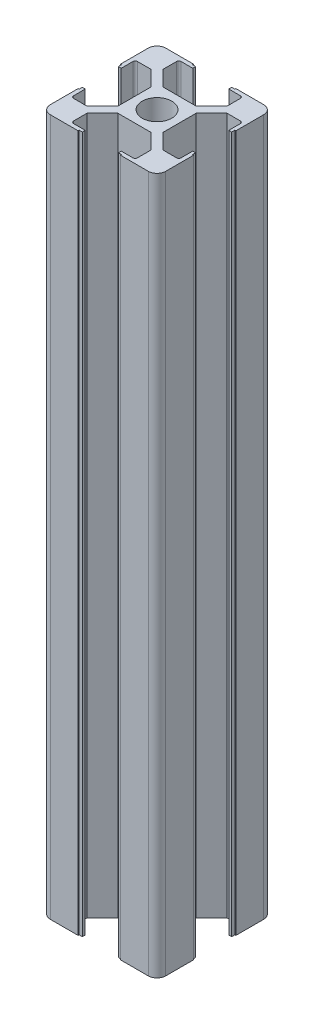
SolidWorks part; units mm, degrees
ref_plane "前视基准面" through (0, 0, 0) normal (0, 0, 1) x (1, 0, 0)
ref_plane "上视基准面" through (0, 0, 0) normal (0, 1, 0) x (1, 0, 0)
ref_plane "右视基准面" through (0, 0, 0) normal (1, 0, 0) x (0, 0, -1)
other "Configuration Table"
ref_plane "基准面1" through (0, 0, 9.9368) normal (0, 0, 1) x (1, 0, 0)
sketch "草图1" plane through (0, 0, 9.9368) normal (0, 0, 1) x (1, 0, 0)
  line L0 (-9.9368, 120) -> (-9.9368, 0)
  line L1 (-9.9368, 0) -> (9.9368, 0)
  line L2 (9.9368, 0) -> (9.9368, 120)
  line L3 (9.9368, 120) -> (-9.9368, 120)
  dimension "D1" = 19.8735
  dimension "D2" = 120
extrude "凸台-拉伸1" add sketch "草图1" against normal blind 19.8735
sketch "草图2" plane through (0, 120, 0) normal (0, 1, 0) x (-1, 0, 0)
  line L0 (-3.65, -9.9368) -> (3.65, -9.9368)
  line L1 (3.65, -9.9368) -> (3.65, -9.76)
  line L2 (3.65, -9.76) -> (3.1, -9.76)
  line L3 (3.1, -9.76) -> (3.1, -9.26)
  line L4 (3.1, -9.26) -> (5.5, -9.26)
  line L5 (5.5, -9.26) -> (5.5, -6.56)
  line L6 (5.5, -6.56) -> (2.84, -3.9)
  line L7 (2.84, -3.9) -> (-2.84, -3.9)
  line L8 (-2.84, -3.9) -> (-5.5, -6.56)
  line L9 (-5.5, -6.56) -> (-5.5, -9.26)
  line L10 (-5.5, -9.26) -> (-3.1, -9.26)
  line L11 (-3.1, -9.26) -> (-3.1, -9.76)
  line L12 (-3.1, -9.76) -> (-3.65, -9.76)
  line L13 (-3.65, -9.76) -> (-3.65, -9.9368)
  line L14 (-9.9368, -9.9368) -> (-9.9368, 9.9368) construction
  line L15 (-9.9368, 9.9368) -> (9.9368, 9.9368) construction
  dimension "D1" = 4.4368
  dimension "D2" = 6.2868
  dimension "D3" = 6.8368
  dimension "D4" = 7.0968
  dimension "D5" = 12.7768
  dimension "D6" = 13.0368
  dimension "D7" = 13.5868
  dimension "D8" = 15.4368
  dimension "D9" = 13.8368
  dimension "D10" = 16.4968
  dimension "D11" = 19.1968
  dimension "D12" = 19.6968
  dimension "D13" = 19.8735
extrude "切除-拉伸1" cut sketch "草图2" against normal through all
sketch "草图3" plane through (0, 120, 0) normal (0, 1, 0) x (-1, 0, 0)
  line L0 (-9.9368, 3.65) -> (-9.9368, -3.65)
  line L1 (-9.9368, -3.65) -> (-9.76, -3.65)
  line L2 (-9.76, -3.65) -> (-9.76, -3.1)
  line L3 (-9.76, -3.1) -> (-9.26, -3.1)
  line L4 (-9.26, -3.1) -> (-9.26, -5.5)
  line L5 (-9.26, -5.5) -> (-6.56, -5.5)
  line L6 (-6.56, -5.5) -> (-3.9, -2.84)
  line L7 (-3.9, -2.84) -> (-3.9, 2.84)
  line L8 (-3.9, 2.84) -> (-6.56, 5.5)
  line L9 (-6.56, 5.5) -> (-9.26, 5.5)
  line L10 (-9.26, 5.5) -> (-9.26, 3.1)
  line L11 (-9.26, 3.1) -> (-9.76, 3.1)
  line L12 (-9.76, 3.1) -> (-9.76, 3.65)
  line L13 (-9.76, 3.65) -> (-9.9368, 3.65)
  line L14 (5.5, -9.26) -> (5.5, -6.56) construction
  line L15 (2.84, -3.9) -> (-2.84, -3.9) construction
  dimension "D1" = 9.4
  dimension "D2" = 12.06
  dimension "D3" = 14.76
  dimension "D4" = 15.26
  dimension "D5" = 15.4368
  dimension "D6" = 0.25
  dimension "D7" = 0.8
  dimension "D8" = 1.06
  dimension "D9" = 6.74
  dimension "D10" = 7
  dimension "D11" = 7.55
  dimension "D12" = 9.4
  dimension "D13" = 1.6
extrude "切除-拉伸2" cut sketch "草图3" against normal blind 120
sketch "草图4" plane through (0, 120, 0) normal (0, 1, 0) x (-1, 0, 0)
  line L0 (3.65, 9.9368) -> (-3.65, 9.9368)
  line L1 (-3.65, 9.9368) -> (-3.65, 9.76)
  line L2 (-3.65, 9.76) -> (-3.1, 9.76)
  line L3 (-3.1, 9.76) -> (-3.1, 9.26)
  line L4 (-3.1, 9.26) -> (-5.5, 9.26)
  line L5 (-5.5, 9.26) -> (-5.5, 6.56)
  line L6 (-5.5, 6.56) -> (-2.84, 3.9)
  line L7 (-2.84, 3.9) -> (2.84, 3.9)
  line L8 (2.84, 3.9) -> (5.5, 6.56)
  line L9 (5.5, 6.56) -> (5.5, 9.26)
  line L10 (5.5, 9.26) -> (3.1, 9.26)
  line L11 (3.1, 9.26) -> (3.1, 9.76)
  line L12 (3.1, 9.76) -> (3.65, 9.76)
  line L13 (3.65, 9.76) -> (3.65, 9.9368)
  line L14 (-3.65, -9.76) -> (-3.65, -9.9368) construction
  line L15 (-9.9368, -9.9368) -> (-3.65, -9.9368) construction
  dimension "D1" = 0.55
  dimension "D2" = 0.81
  dimension "D3" = 6.49
  dimension "D4" = 6.75
  dimension "D5" = 7.3
  dimension "D6" = 9.15
  dimension "D7" = 1.85
  dimension "D8" = 13.8368
  dimension "D9" = 16.4968
  dimension "D10" = 19.1968
  dimension "D11" = 19.6968
  dimension "D12" = 19.8735
extrude "切除-拉伸3" cut sketch "草图4" against normal through all
sketch "草图5" plane through (0, 120, 0) normal (0, 1, 0) x (-1, 0, 0)
  line L0 (9.9368, -3.65) -> (9.9368, 3.65)
  line L1 (9.9368, 3.65) -> (9.76, 3.65)
  line L2 (9.76, 3.65) -> (9.76, 3.1)
  line L3 (9.76, 3.1) -> (9.26, 3.1)
  line L4 (9.26, 3.1) -> (9.26, 5.5)
  line L5 (9.26, 5.5) -> (6.56, 5.5)
  line L6 (6.56, 5.5) -> (3.9, 2.84)
  line L7 (3.9, 2.84) -> (3.9, -2.84)
  line L8 (3.9, -2.84) -> (6.56, -5.5)
  line L9 (6.56, -5.5) -> (9.26, -5.5)
  line L10 (9.26, -5.5) -> (9.26, -3.1)
  line L11 (9.26, -3.1) -> (9.76, -3.1)
  line L12 (9.76, -3.1) -> (9.76, -3.65)
  line L13 (9.76, -3.65) -> (9.9368, -3.65)
  line L14 (5.5, 6.56) -> (5.5, 9.26) construction
  line L16 (-9.9368, 9.9368) -> (-3.65, 9.9368) construction
  dimension "D1" = 1.06
  dimension "D2" = 3.76
  dimension "D3" = 4.26
  dimension "D4" = 4.4368
  dimension "D5" = 1.6
  dimension "D6" = 4.4368
  dimension "D7" = 6.2868
  dimension "D8" = 6.8368
  dimension "D9" = 7.0968
  dimension "D10" = 12.7768
  dimension "D11" = 13.0368
  dimension "D12" = 13.5868
  dimension "D13" = 15.4368
extrude "切除-拉伸4" cut sketch "草图5" against normal through all
hole_wizard "Ø5.0 (5) 直径孔1" positions "草图7" profile "草图6" hole size "Ø5.0" standard "ANSI Metric"
sketch "草图7" plane through (-3.9, 0, 0) normal (-1, 0, 0) x (0, 0, 1)
  point P0 (0, 12)
sketch "草图6" plane through (-3.9, 12, 0) normal (0, 1, 0) x (0, 0, 1)
  line L0 (0, 0) -> (0, 7.8)
  line L1 (0, 7.8) -> (2.5, 7.8)
  line L2 (2.5, 7.8) -> (2.5, 0)
  line L5 (2.5, 0) -> (0, 0)
  line L10 (0, 7.8) -> (-2.5, 7.8) construction
  line L11 (0, -6.35) -> (0, 107.95) construction
  dimension "孔直径" = 5
  dimension "孔深度" = 7.8
  dimension "导头角度" = 180
hole_wizard "Ø5.0 (5) 直径孔2" positions "草图9" profile "草图8" hole size "Ø5.0" standard "ANSI Metric"
sketch "草图9" plane through (3.9, 0, 0) normal (1, 0, 0) x (0, 0, -1)
  point P0 (0, 68)
sketch "草图8" plane through (3.9, 68, 0) normal (0, 1, 0) x (0, 0, -1)
  line L0 (0, 0) -> (0, 7.8)
  line L1 (0, 7.8) -> (2.5, 7.8)
  line L2 (2.5, 7.8) -> (2.5, 0)
  line L5 (2.5, 0) -> (0, 0)
  line L10 (0, 7.8) -> (-2.5, 7.8) construction
  line L11 (0, -6.35) -> (0, 107.95) construction
  dimension "孔直径" = 5
  dimension "孔深度" = 7.8
  dimension "导头角度" = 180
hole_wizard "Ø5.0 (5) 直径孔3" positions "草图11" profile "草图10" hole size "Ø5.0" standard "ANSI Metric"
sketch "草图11" plane through (0, 0, -3.9) normal (0, 0, -1) x (-1, 0, 0)
  point P0 (0, 108)
sketch "草图10" plane through (0, 108, -3.9) normal (1, 0, 0) x (0, 1, 0)
  line L0 (0, 0) -> (0, 7.8)
  line L1 (0, 7.8) -> (2.5, 7.8)
  line L2 (2.5, 7.8) -> (2.5, 0)
  line L5 (2.5, 0) -> (0, 0)
  line L10 (0, 7.8) -> (-2.5, 7.8) construction
  line L11 (0, -6.35) -> (0, 107.95) construction
  dimension "孔直径" = 5
  dimension "孔深度" = 7.8
  dimension "导头角度" = 180
hole_wizard "Ø5.0 (5) 直径孔4" positions "草图13" profile "草图12" hole size "Ø5.0" standard "ANSI Metric"
sketch "草图13" plane through (0, 0, -3.9) normal (0, 0, -1) x (-1, 0, 0)
  point P0 (0, 68)
sketch "草图12" plane through (0, 68, -3.9) normal (1, 0, 0) x (0, 1, 0)
  line L0 (0, 0) -> (0, 11.7)
  line L1 (0, 11.7) -> (2.5, 11.7)
  line L2 (2.5, 11.7) -> (2.5, 0)
  line L5 (2.5, 0) -> (0, 0)
  line L10 (0, 11.7) -> (-2.5, 11.7) construction
  line L11 (0, -6.35) -> (0, 107.95) construction
  dimension "孔直径" = 5
  dimension "孔深度" = 11.7
  dimension "导头角度" = 180
hole_wizard "Ø5.0 (5) 直径孔5" positions "草图15" profile "草图14" hole size "Ø5.0" standard "ANSI Metric"
sketch "草图15" plane through (-3.9, 0, 0) normal (-1, 0, 0) x (0, 0, 1)
  point P0 (0, 108)
sketch "草图14" plane through (-3.9, 108, 0) normal (0, 1, 0) x (0, 0, 1)
  line L0 (0, 0) -> (0, 11.7)
  line L1 (0, 11.7) -> (2.5, 11.7)
  line L2 (2.5, 11.7) -> (2.5, 0)
  line L5 (2.5, 0) -> (0, 0)
  line L10 (0, 11.7) -> (-2.5, 11.7) construction
  line L11 (0, -6.35) -> (0, 107.95) construction
  dimension "孔直径" = 5
  dimension "孔深度" = 11.7
  dimension "导头角度" = 180
hole_wizard "Ø5.0 (5) 直径孔6" positions "草图17" profile "草图16" hole size "Ø5.0" standard "ANSI Metric"
sketch "草图17" plane through (0, 0, 3.9) normal (0, 0, 1) x (1, 0, 0)
  point P0 (0, 12)
sketch "草图16" plane through (0, 12, 3.9) normal (1, 0, 0) x (0, -1, 0)
  line L0 (0, 0) -> (0, 11.7)
  line L1 (0, 11.7) -> (2.5, 11.7)
  line L2 (2.5, 11.7) -> (2.5, 0)
  line L5 (2.5, 0) -> (0, 0)
  line L10 (0, 11.7) -> (-2.5, 11.7) construction
  line L11 (0, -6.35) -> (0, 107.95) construction
  dimension "孔直径" = 5
  dimension "孔深度" = 11.7
  dimension "导头角度" = 180
hole_wizard "Ø5.1 (5.1) 直径孔1" positions "草图19" profile "草图18" hole size "Ø5.1" standard "ANSI Metric"
sketch "草图19" plane through (0, 120, 0) normal (0, 1, 0) x (1, 0, 0)
  point P0 (0, 0)
sketch "草图18" plane through (0, 120, 0) normal (1, 0, 0) x (0, 0, 1)
  line L0 (0, 0) -> (0, 226.2683)
  line L1 (0, 226.2683) -> (2.55, 226.2683)
  line L2 (2.55, 226.2683) -> (2.55, 0)
  line L5 (2.55, 0) -> (0, 0)
  line L10 (0, 226.2683) -> (-2.55, 226.2683) construction
  line L11 (0, -6.35) -> (0, 107.95) construction
  dimension "孔直径" = 5.1
  dimension "孔深度" = 226.2683
  dimension "导头角度" = 180
fillet "圆角1" radius 0.4 8 edges at (9.26, 60, 5.5) (5.5, 60, -9.26) (-5.5, 60, -9.26) (9.26, 60, -5.5) (-9.26, 60, 5.5) (-9.26, 60, -5.5) (-5.5, 60, 9.26) (5.5, 60, 9.26)
fillet "圆角2" radius 1.5 4 edges at (-9.9368, 60, -9.9368) (9.9368, 60, -9.9368) (-9.9368, 60, 9.9368) (9.9368, 60, 9.9368)
